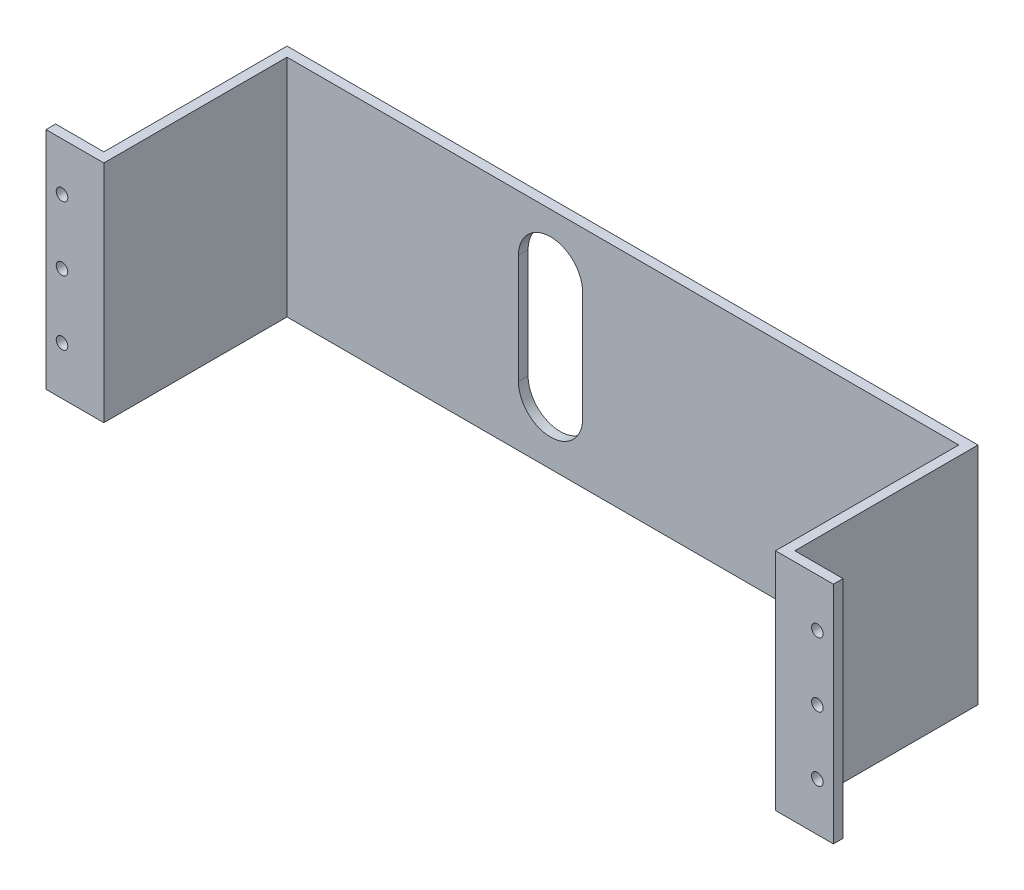
SolidWorks part; units mm, degrees
ref_plane "Front Plane" through (0, 0, 0) normal (0, 0, 1) x (1, 0, 0)
ref_plane "Top Plane" through (0, 0, 0) normal (0, 1, 0) x (1, 0, 0)
ref_plane "Right Plane" through (0, 0, 0) normal (1, 0, 0) x (0, 0, -1)
sketch "Sketch1" plane through (0, 0, 0) normal (0, 1, 0) x (1, 0, 0)
  line L0 (0, 0) -> (18, 0)
  line L1 (18, 0) -> (18, 57)
  line L2 (227, 57) -> (18, 57)
  line L3 (0, 0) -> (0, 3)
  line L4 (0, 3) -> (15, 3)
  line L5 (15, 3) -> (15, 60)
  line L6 (15, 60) -> (230, 60)
  line L7 (122.5, 41.705) -> (122.5, 38.705) construction
  line L8 (230, 3) -> (230, 60)
  line L9 (245, 3) -> (230, 3)
  line L10 (245, 0) -> (245, 3)
  line L11 (227, 0) -> (227, 57)
  line L12 (245, 0) -> (227, 0)
  point P12 (122.5, 60)
  point P16 (122.5, 57)
  dimension "D1" = 3
  dimension "D2" = 3
  dimension "D3" = 3
  dimension "D4" = 18
  dimension "D5" = 122.5
  dimension "D6" = 60
extrude "Boss-Extrude1" add sketch "Sketch1" along normal blind 70
sketch "Sketch2" plane through (0, 0, -3) normal (0, 0, -1) x (-1, 0, 0)
  line L0 (-245, 70) -> (-230, 70) construction
  line L1 (-122.5, 70) -> (-122.5, 0) construction
  line L2 (-230, 70) -> (-15, 70) construction
  line L3 (-230, 0) -> (-15, 0) construction
  circle A0 centre (-240.02, 55) radius 1.8
  circle A1 centre (-240.02, 35) radius 1.8
  circle A2 centre (-240.02, 15) radius 1.8
  circle A3 centre (-4.98, 15) radius 1.8
  circle A4 centre (-4.98, 35) radius 1.8
  circle A5 centre (-4.98, 55) radius 1.8
  dimension "D1" = 20
  dimension "D2" = 20
  dimension "D3" = 15
  dimension "D4" = 117.52
extrude "Cut-Extrude1" cut sketch "Sketch2" against normal through all
sketch "Sketch3" plane through (0, 0, -57) normal (0, 0, 1) x (1, 0, 0)
  line L0 (100, 52.6161) -> (100, 18.6333) construction
  line L1 (110, 52.6161) -> (110, 18.6333)
  line L2 (90, 52.6161) -> (90, 18.6333)
  line L3 (18, 70) -> (18, 0) construction
  arc A0 (110, 52.6161) -> (90, 52.6161) centre (100, 52.6161) ccw
  arc A1 (90, 18.6333) -> (110, 18.6333) centre (100, 18.6333) ccw
  point P2 (100, 35.6247)
  dimension "D1" = 82
extrude "Cut-Extrude2" cut sketch "Sketch3" against normal up to next
